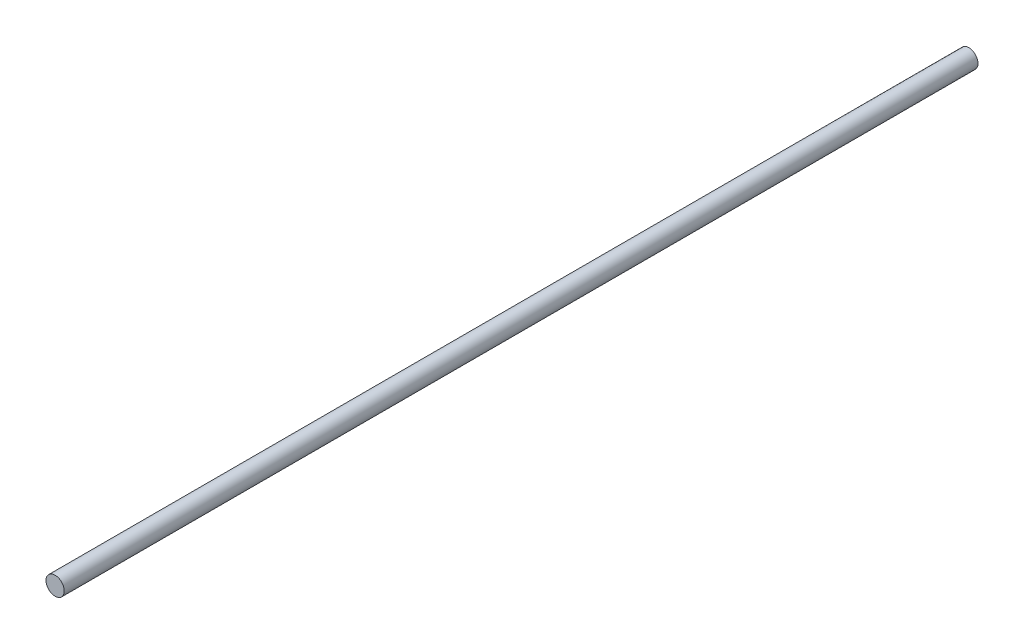
SolidWorks part; units mm, degrees
ref_plane "Plan de face" through (0, 0, 0) normal (0, 0, 1) x (1, 0, 0)
ref_plane "Plan de dessus" through (0, 0, 0) normal (0, 1, 0) x (1, 0, 0)
ref_plane "Plan de droite" through (0, 0, 0) normal (1, 0, 0) x (0, 0, -1)
sketch "Esquisse1" plane through (0, 0, 0) normal (0, 0, 1) x (1, 0, 0)
  circle A0 centre (0, 0) radius 1
  dimension "D1" = 2
extrude "Boss.-Extru.1" add sketch "Esquisse1" along normal blind 100
